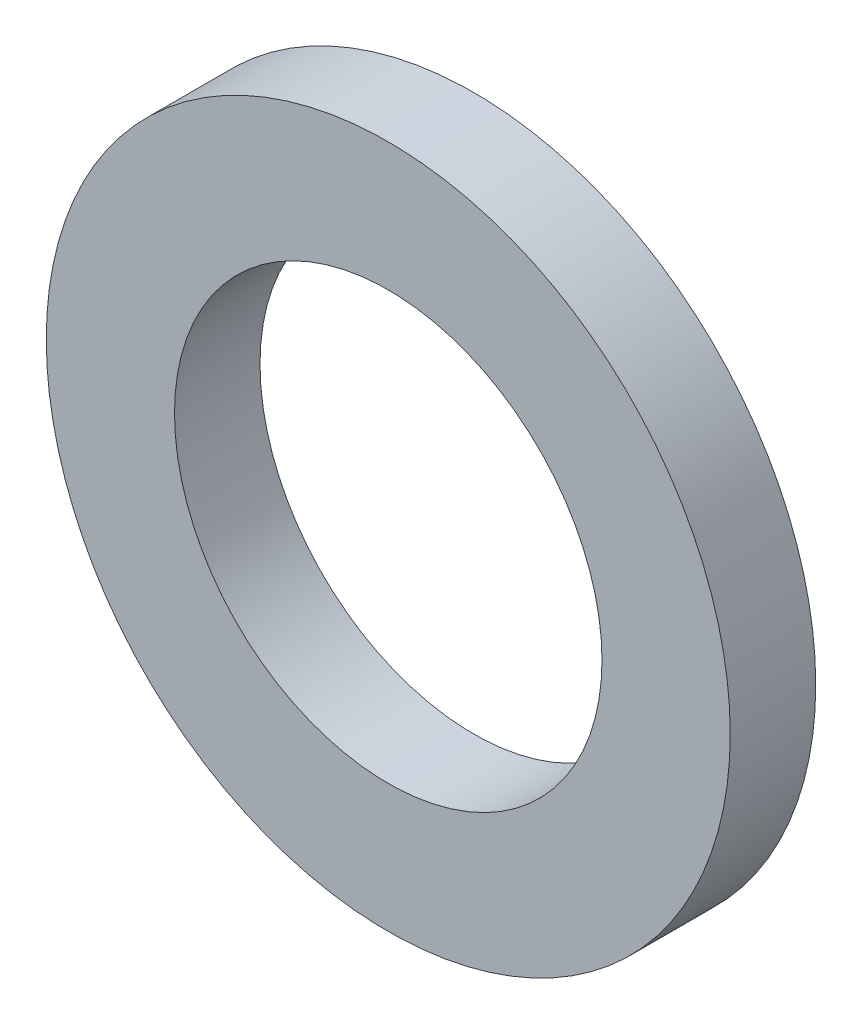
SolidWorks part; units mm, degrees
material "PTFE (general)"
ref_plane "Front Plane" through (0, 0, 0) normal (0, 0, 1) x (1, 0, 0)
ref_plane "Top Plane" through (0, 0, 0) normal (0, 1, 0) x (1, 0, 0)
ref_plane "Right Plane" through (0, 0, 0) normal (1, 0, 0) x (0, 0, -1)
sketch "Sketch1" plane through (0, 0, 0) normal (0, 0, 1) x (1, 0, 0)
  circle A0 centre (0, 0) radius 7.9375
  circle A1 centre (0, 0) radius 12.7
  dimension "D1" = 15.875
  dimension "D2" = 25.4
extrude "Boss-Extrude1" add sketch "Sketch1" along normal blind 3.175
